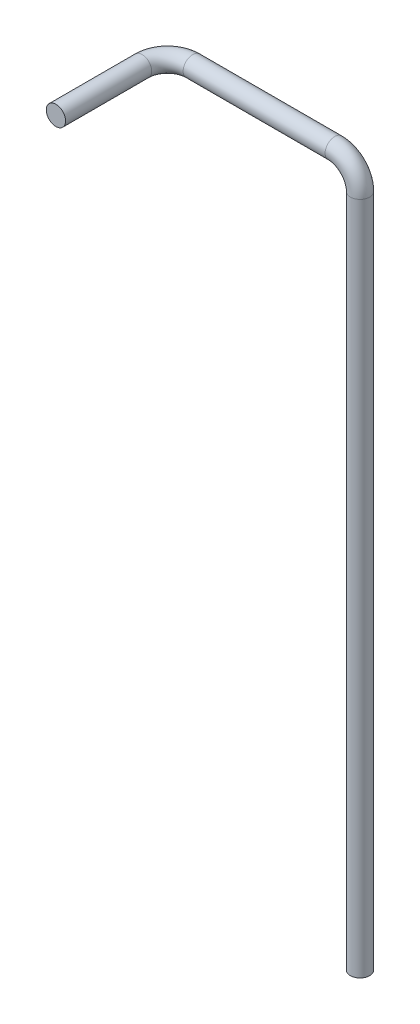
SolidWorks part; units mm, degrees
ref_plane "Alzado" through (0, 0, 0) normal (0, 0, 1) x (1, 0, 0)
ref_plane "Planta" through (0, 0, 0) normal (0, 1, 0) x (1, 0, 0)
ref_plane "Vista lateral" through (0, 0, 0) normal (1, 0, 0) x (0, 0, -1)
sketch "Croquis1" plane through (0, 0, 0) normal (0, 1, 0) x (1, 0, 0)
  circle A0 centre (0, 0) radius 9.525
  dimension "D1" = 19.05
extrude "Saliente-Extruir1" add sketch "Croquis1" along normal blind 10
sketch3d "Croquis3D1"
  line L0 (0, 10, 0) -> (0, 665, 0)
  line L1 (0, 10, 0) -> (0, 0, 0) construction
  line L2 (-25, 690, 0) -> (-165, 690, 0)
  line L3 (-190, 690, 25) -> (-190, 690, 110)
  arc A1 (-165, 690, 0) -> (-190, 690, 25) centre (-165, 690, 25) ccw
  arc A2 (0, 665, 0) -> (-25, 690, 0) centre (-25, 665, 0) ccw
  point P9 (-190, 690, 219)
  point P13 (-190, 690, 0)
  point P14 (-165, 715, 25)
  point P17 (0, 690, 0)
  point P18 (-25, 665, 25)
  dimension "D1" = 680
  dimension "D2" = 190
  dimension "D3" = 219
  dimension "D4" = 110
sketch "Croquis2" plane through (0, 10, 0) normal (0, 1, 0) x (1, 0, 0)
  circle A0 centre (0, 0) radius 9.525
sweep "Barrer1" add profiles "Croquis2" path "Croquis3D1"
